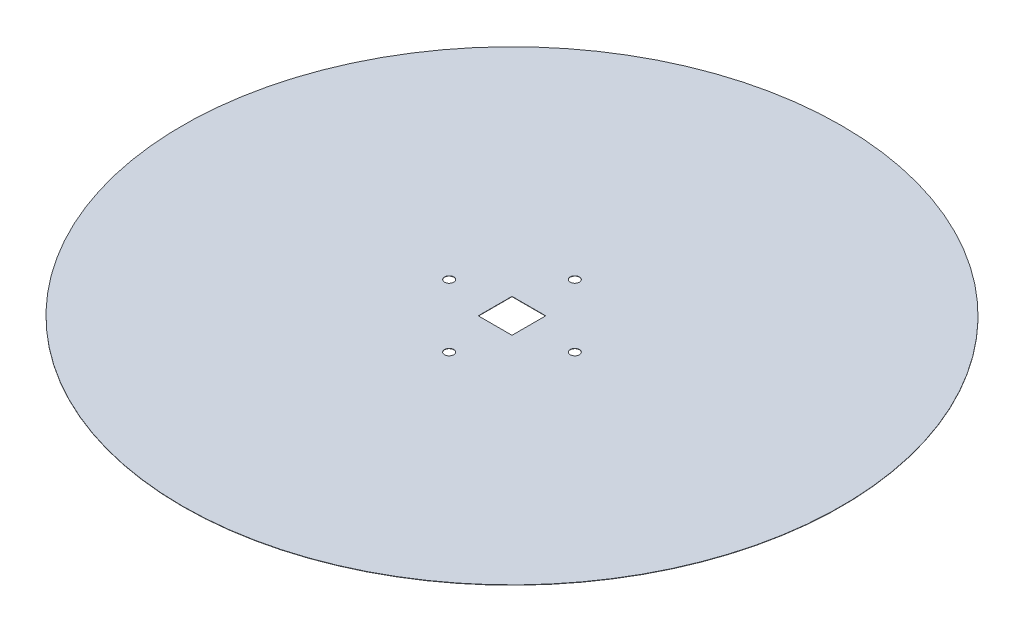
SolidWorks part; units mm, degrees
material "Сетка Алюмминиевая"
ref_plane "Front" through (0, 0, 0) normal (0, 0, 1) x (1, 0, 0)
ref_plane "Top" through (0, 0, 0) normal (0, 1, 0) x (1, 0, 0)
ref_plane "Right" through (0, 0, 0) normal (1, 0, 0) x (0, 0, -1)
sketch "Эскиз1" plane through (0, 0, 0) normal (0, 1, 0) x (1, 0, 0)
  circle A0 centre (0, 0) radius 215
  dimension "D1" = 430
extrude "Бобышка-Вытянуть1" add sketch "Эскиз1" along normal blind 0.2
sketch "Эскиз4" plane through (0, 0.2, 0) normal (0, 1, 0) x (1, 0, 0)
  line L0 (0, 66) -> (0, 16) construction
  line L1 (0, 133.2551) -> (0, -39.4493) construction
  line L2 (-11, 11) -> (11, 11)
  line L3 (-11, 11) -> (-11, -11)
  line L4 (-11, -11) -> (11, -11)
  line L5 (11, 11) -> (11, -11)
  line L6 (-11, 11) -> (11, -11) construction
  line L7 (-11, -11) -> (11, 11) construction
  line L8 (-16, 16) -> (16, 16)
  line L9 (-16, 16) -> (-16, -16)
  line L10 (-16, -16) -> (16, -16)
  line L11 (16, 16) -> (16, -16)
  line L12 (-16, 16) -> (16, -16) construction
  line L13 (-16, -16) -> (16, 16) construction
  circle A2 centre (0, 41) radius 3
  circle A4 centre (41, 0) radius 3
  circle A5 centre (0, -41) radius 3
  circle A6 centre (-41, 0) radius 3
  point P0 (0, 0)
  point P11 (0, 41)
  point P14 (0, 0)
  point P28 (0, 0)
  dimension "D1" = 22
  dimension "D2" = 22
  dimension "D3" = 6
  dimension "D4" = 5
  dimension "D5" = 5
  dimension "D6" = 25
  dimension "D8" = 25
  dimension "D9" = 25
  dimension "D7" = 4
extrude "Вырез-Вытянуть2" cut sketch "Эскиз4" against normal up to next contours A2 | L3 L4 L5 L2 | A5 | A4 | A6
